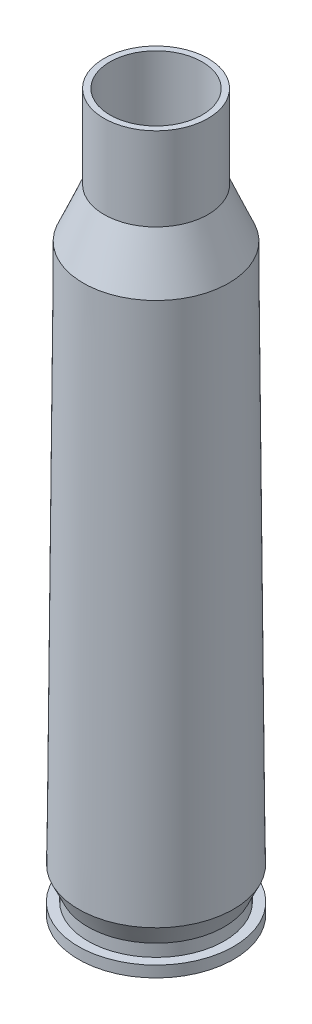
SolidWorks part; units mm, degrees
ref_plane "Plan de face" through (0, 0, 0) normal (0, 0, 1) x (1, 0, 0)
ref_plane "Plan de dessus" through (0, 0, 0) normal (0, 1, 0) x (1, 0, 0)
ref_plane "Plan de droite" through (0, 0, 0) normal (1, 0, 0) x (0, 0, -1)
sketch "Esquisse1" plane through (0, 0, 0) normal (0, 0, 1) x (1, 0, 0)
  line L0 (-2.85, 39.4412) -> (-2.85, 44.7)
  line L1 (-3.215, 44.7) -> (-3.215, 39.55)
  line L2 (-3.215, 39.55) -> (-4.5, 36.52)
  line L3 (-4.5, 36.52) -> (-4.79, 3.13)
  line L4 (-2.85, 44.7) -> (-3.215, 44.7)
  line L5 (-2.85, 39.4412) -> (-3.942, 36.3214)
  line L6 (-3.942, 36.3214) -> (-3.942, 3.13)
  line L7 (-3.3685, 1.14) -> (0, 1.14)
  line L8 (0, 1.14) -> (0, 0)
  line L9 (0, 0) -> (-4.1573, 0)
  line L10 (-4.8, 1.14) -> (-4.8, 0.45)
  line L11 (-4.8, 1.14) -> (-4.2164, 1.14)
  line L12 (-4.2164, 1.14) -> (-4.2164, 1.9)
  line L13 (-4.2164, 1.9) -> (-4.79, 3.13)
  line L14 (0, 0) -> (0, 73.5844) construction
  line L15 (-3.3685, 1.14) -> (-3.3685, 1.9)
  line L16 (-3.3685, 1.9) -> (-3.942, 3.13)
  line L17 (-4.8, 0.45) -> (-4.1573, 0)
  dimension "D1" = 35
  dimension "D2" = 44.7
  dimension "D3" = 39.55
  dimension "D4" = 36.52
  dimension "D5" = 9.6
  dimension "D6" = 3.13
  dimension "D7" = 0.76
  dimension "D8" = 25
  dimension "D9" = 0.45
  dimension "D10" = 1.14
  dimension "D11" = 4.5
  dimension "D12" = 4.79
  dimension "D13" = 6.43
  dimension "D14" = 6.43
  dimension "D15" = 5.7
revolve "Révolution1" add sketch "Esquisse1" angle 360 about L14
equation "\"D2@Esquisse1\"=\"L3@Calibre.SLDASM\""
equation "\"D3@Esquisse1\"=\"L2@Calibre.SLDASM\""
equation "\"D4@Esquisse1\"=\"L1@Calibre.SLDASM\""
equation "\"D6@Esquisse1\"=\"E2@Calibre.SLDASM\""
equation "\"D7@Esquisse1\"=\"e@Calibre.SLDASM\""
equation "\"D9@Esquisse1\"=\"f@Calibre.SLDASM\""
equation "\"D10@Esquisse1\"=\"R@Calibre.SLDASM\""
equation "\"D11@Esquisse1\"=\"P2@Calibre.SLDASM\"/2"
equation "\"D12@Esquisse1\"=\"P1@Calibre.SLDASM\"/2"
equation "\"D13@Esquisse1\"=\"H2@Calibre.SLDASM\""
equation "\"D14@Esquisse1\"=\"H1@Calibre.SLDASM\""
equation "\"D5@Esquisse1\"=\"R1@Calibre.SLDASM\""
equation "\"D15@Esquisse1\"=\"G1@Calibre.SLDASM\""
equation "\"D1@Esquisse1\"=\"beta@Calibre.SLDASM\""
equation "\"D8@Esquisse1\"=\"delta@Calibre.SLDASM\""
